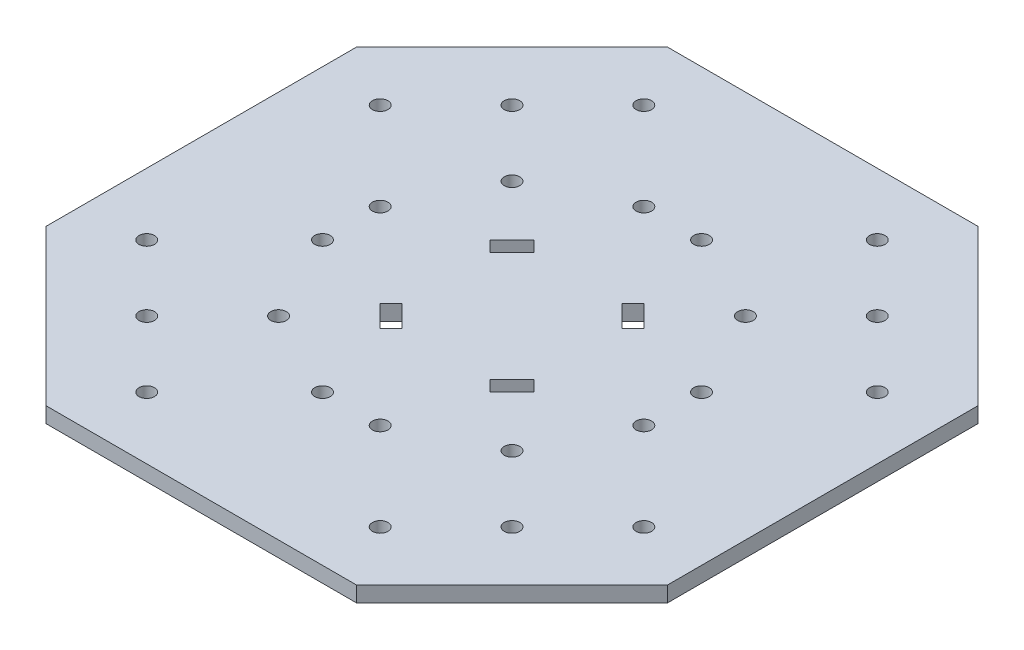
SolidWorks part; units mm, degrees
material "Custom Plastic"
ref_plane "Front Plane" through (0, 0, 0) normal (0, 0, 1) x (1, 0, 0)
ref_plane "Top Plane" through (0, 0, 0) normal (0, 1, 0) x (1, 0, 0)
ref_plane "Right Plane" through (0, 0, 0) normal (1, 0, 0) x (0, 0, -1)
sketch "Sketch1" plane through (0, 0, 0) normal (0, 1, 0) x (1, 0, 0)
  line L1 (0, 0) -> (200, 0)
  line L2 (0, 0) -> (0, 200)
  line L3 (0, 200) -> (200, 200)
  line L4 (200, 0) -> (200, 200)
  dimension "D1" = 200
  dimension "D2" = 200
extrude "Boss-Extrude1" add sketch "Sketch1" along normal blind 5
sketch "Sketch3" plane through (0, 5, 0) normal (0, 1, 0) x (1, 0, 0)
  line L0 (0, 200) -> (200, 0) construction
  line L1 (0, 200) -> (200, 200)
  line L2 (0, 200) -> (0, 0)
  line L3 (0, 0) -> (200, 0)
  line L4 (200, 200) -> (200, 0)
  line L5 (200, 200) -> (0, 0) construction
  circle A0 centre (62.4264, 180) radius 2.5
  circle A1 centre (90.7107, 151.7157) radius 2.5
  circle A2 centre (48.2843, 109.2893) radius 2.5
  circle A3 centre (20, 137.5736) radius 2.5
  circle A4 centre (100, 100) radius 10
  circle A5 centre (180, 137.5736) radius 2.5
  circle A6 centre (151.7157, 109.2893) radius 2.5
  circle A7 centre (109.2893, 151.7157) radius 2.5
  circle A8 centre (137.5736, 180) radius 2.5
  circle A9 centre (137.5736, 20) radius 2.5
  circle A10 centre (109.2893, 48.2843) radius 2.5
  circle A11 centre (151.7157, 90.7107) radius 2.5
  circle A12 centre (180, 62.4264) radius 2.5
  circle A13 centre (20, 62.4264) radius 2.5
  circle A14 centre (48.2843, 90.7107) radius 2.5
  circle A15 centre (90.7107, 48.2843) radius 2.5
  circle A16 centre (62.4264, 20) radius 2.5
  point P43 (100, 100)
  dimension "D5" = 5
  dimension "D6" = 5
  dimension "D7" = 20
  dimension "D1" = 30
  dimension "D2" = 30
  dimension "D3" = 40
  dimension "D4" = 20
  dimension "D8" = 4
extrude "Cut-Extrude2" cut sketch "Sketch3" against normal blind 5 contours A12 | A15 | A10 | A16 | A9 | A13 | A14 | A3 | A2 | A0 | A1 | A7 | A8 | A5 | A6 | A11
sketch "Sketch4" plane through (0, 5, 0) normal (0, 1, 0) x (1, 0, 0)
  line L0 (0, 0) -> (200, 200) construction
  line L1 (200, 0) -> (0, 200) construction
  line L2 (100, 64.6447) -> (135.3553, 100)
  line L3 (135.3553, 100) -> (100, 135.3553)
  line L4 (100, 135.3553) -> (64.6447, 100)
  line L5 (64.6447, 100) -> (100, 64.6447)
  line L6 (100, 57.5736) -> (142.4264, 100)
  line L7 (142.4264, 100) -> (100, 142.4264)
  line L8 (100, 142.4264) -> (57.5736, 100)
  line L9 (57.5736, 100) -> (100, 57.5736)
  line L10 (124.7487, 82.3223) -> (121.2132, 85.8579)
  line L11 (117.6777, 75.2513) -> (114.1421, 78.7868)
  line L12 (75.2513, 82.3223) -> (78.7868, 85.8579)
  line L13 (82.3223, 75.2513) -> (85.8579, 78.7868)
  line L14 (82.3223, 124.7487) -> (85.8579, 121.2132)
  line L15 (75.2513, 117.6777) -> (78.7868, 114.1421)
  line L16 (124.7487, 117.6777) -> (121.2132, 114.1421)
  line L17 (117.6777, 124.7487) -> (114.1421, 121.2132)
  circle A0 centre (100, 100) radius 7.9568
  point P37 (100, 100)
  dimension "D8" = 15.9135
  dimension "D1" = 50
  dimension "D2" = 50
  dimension "D3" = 25
  dimension "D4" = 25
  dimension "D6" = 5
  dimension "D7" = 5
  dimension "D5" = 5
  dimension "D9" = 4
extrude "Cut-Extrude4" cut sketch "Sketch4" against normal blind 200 contours L7 L17 L3 L16 | L11 L6 L10 L2 | L9 L13 L5 L12 | L8 L15 L4 L14
chamfer "Chamfer1" distance 50 angle 45 4 edges at (200, 2.5, 0) (200, 2.5, -200) (0, 2.5, -200) (0, 2.5, 0)
sketch "Sketch5" plane through (0, 5, 0) normal (0, 1, 0) x (1, 0, 0)
  line L0 (62.4264, 20) -> (20, 62.4264) construction
  line L1 (20, 62.4264) -> (48.2843, 90.7107) construction
  line L2 (48.2843, 90.7107) -> (90.7107, 48.2843) construction
  line L3 (90.7107, 48.2843) -> (62.4264, 20) construction
  line L4 (82.3223, 82.3223) -> (82.3223, 117.6777) construction
  line L5 (78.7868, 85.8579) -> (85.8579, 78.7868) construction
  line L6 (85.8579, 121.2132) -> (78.7868, 114.1421) construction
  line L7 (82.3223, 117.6777) -> (117.6777, 117.6777) construction
  line L8 (121.2132, 114.1421) -> (114.1421, 121.2132) construction
  line L9 (117.6777, 117.6777) -> (117.6777, 82.3223) construction
  line L10 (114.1421, 78.7868) -> (121.2132, 85.8579) construction
  line L11 (117.6777, 82.3223) -> (82.3223, 82.3223) construction
  circle A0 centre (41.2132, 41.2132) radius 2.5
  circle A1 centre (62.4264, 137.5736) radius 2.5
  circle A2 centre (41.2132, 158.7868) radius 2.5
  circle A3 centre (137.5736, 137.5736) radius 2.5
  circle A4 centre (158.7868, 158.7868) radius 2.5
  circle A5 centre (137.5736, 62.4264) radius 2.5
  circle A6 centre (158.7868, 41.2132) radius 2.5
  circle A8 centre (62.4264, 62.4264) radius 2.5
  point P18 (100, 100)
  point P40 (100, 100)
  point P41 (100, 100)
  dimension "D1" = 5
  dimension "D2" = 4
  dimension "D4" = 5
  dimension "D3" = 4
extrude "Cut-Extrude5" cut sketch "Sketch5" against normal blind 10
